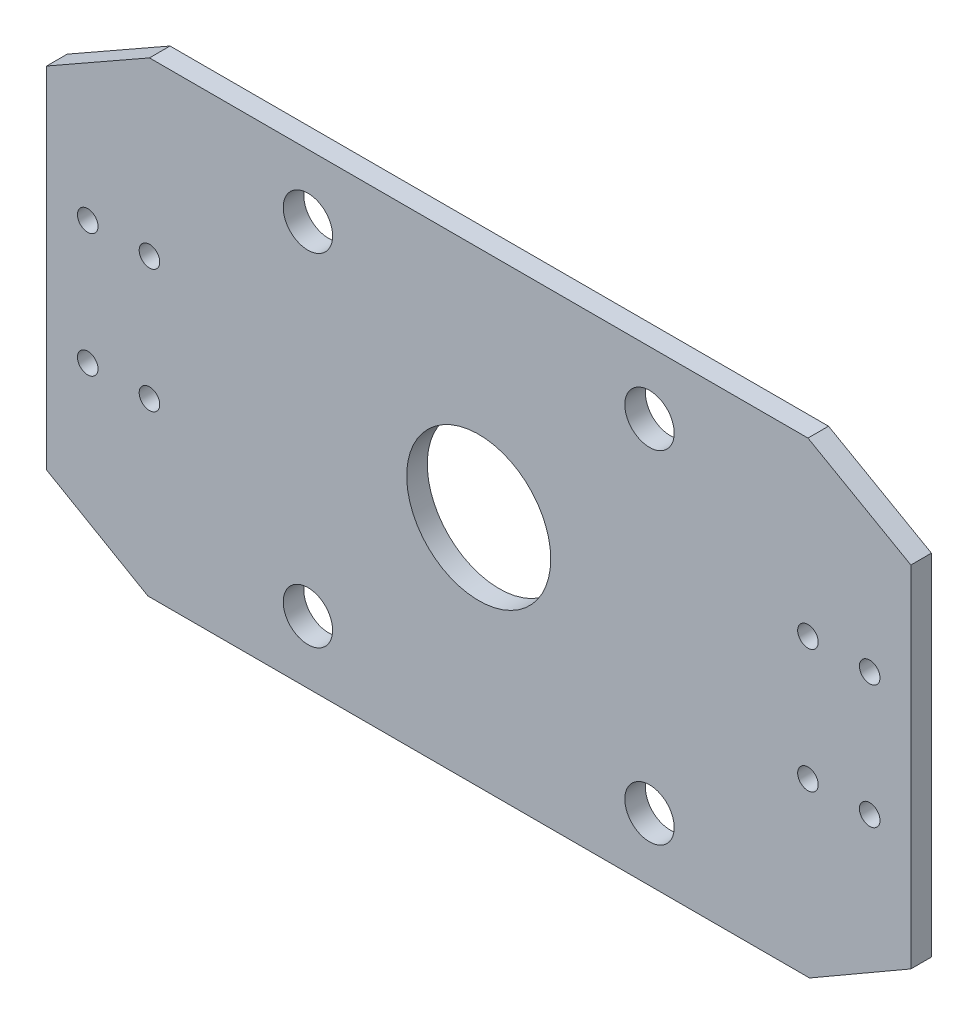
SolidWorks part; units mm, degrees
ref_plane "Front Plane" through (0, 0, 0) normal (0, 0, 1) x (1, 0, 0)
ref_plane "Top Plane" through (0, 0, 0) normal (0, 1, 0) x (1, 0, 0)
ref_plane "Right Plane" through (0, 0, 0) normal (1, 0, 0) x (0, 0, -1)
sketch "Sketch1" plane through (0, 0, 0) normal (0, 0, 1) x (1, 0, 0)
  line L0 (0, 55.807) -> (0, -57.6167) construction
  line L1 (80, 55.807) -> (-80, 55.807)
  line L2 (-80, 55.807) -> (-105, 41.5951)
  line L3 (-105, 41.5951) -> (-105, -43.4049)
  line L4 (-105, -43.4049) -> (-80.3844, -57.6167)
  line L5 (-80.3844, -57.6167) -> (80.3844, -57.6167)
  line L6 (105, -43.4049) -> (80.3844, -57.6167)
  line L7 (105, 41.5951) -> (105, -43.4049)
  line L8 (80, 55.807) -> (105, 41.5951)
  line L9 (-105, -0.9049) -> (105, -0.9049) construction
  line L10 (-95, 14.0951) -> (-95, -15.9049) construction
  line L11 (-95, -15.9049) -> (-80, -15.9049) construction
  line L12 (-80, -15.9049) -> (-80, 14.0951) construction
  line L13 (-80, 14.0951) -> (-95, 14.0951) construction
  line L14 (-87.5, 14.0951) -> (-87.5, -15.9049) construction
  circle A0 centre (0, -0.9049) radius 17.5
  circle A1 centre (-95, 14.0951) radius 2.5
  circle A2 centre (-80, 14.0951) radius 2.5
  circle A3 centre (-95, -15.9049) radius 2.5
  circle A4 centre (-80, -15.9049) radius 2.5
  circle A5 centre (80, -15.9049) radius 2.5
  circle A6 centre (95, -15.9049) radius 2.5
  circle A7 centre (95, 14.0951) radius 2.5
  circle A8 centre (80, 14.0951) radius 2.5
  circle A9 centre (-41.5, 40.5951) radius 6
  circle A10 centre (41.5, 40.5951) radius 6
  circle A11 centre (41.5, -42.4049) radius 6
  circle A12 centre (-41.5, -42.4049) radius 6
  point P10 (0, -57.6167)
  point P13 (0, 55.807)
  point P44 (0, -0.9049)
  dimension "D6" = 35
  dimension "D7" = 5
  dimension "D8" = 5
  dimension "D9" = 5
  dimension "D10" = 5
  dimension "D2" = 41.5
  dimension "D1" = 80
  dimension "D3" = 41.5
  dimension "D4" = 10
  dimension "D5" = 85
  dimension "D11" = 15
  dimension "D12" = 15
  dimension "D13" = 15
  dimension "D14" = 15
  dimension "D15" = 4
  dimension "D16" = 15
  dimension "D17" = 41.5
  dimension "D18" = 41.5
  dimension "D19" = 210
extrude "Boss-Extrude1" add sketch "Sketch1" along normal blind 5
